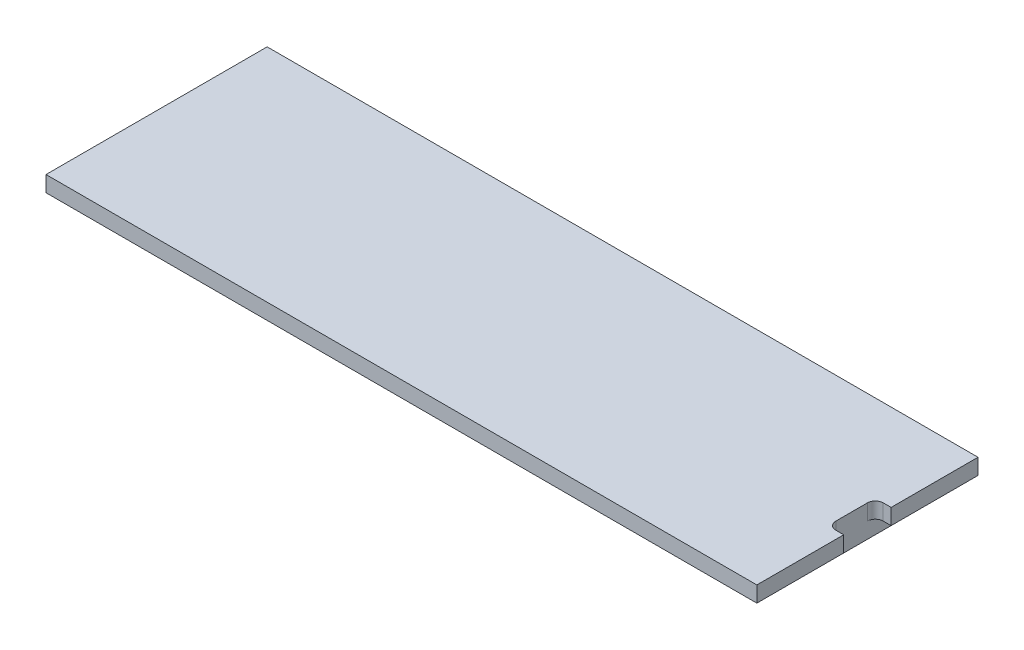
SolidWorks part; units mm, degrees
ref_plane "Front Plane" through (0, 0, 0) normal (0, 0, 1) x (1, 0, 0)
ref_plane "Top Plane" through (0, 0, 0) normal (0, 1, 0) x (1, 0, 0)
ref_plane "Right Plane" through (0, 0, 0) normal (1, 0, 0) x (0, 0, -1)
sketch "Sketch1" plane through (0, 0, 0) normal (0, 1, 0) x (1, 0, 0)
  line L1 (-20.5, -6) -> (20.5, -6)
  line L2 (-21.5, -5) -> (-21.5, 5)
  line L3 (-20.5, 6) -> (20.5, 6)
  line L4 (21.5, -5) -> (21.5, 5)
  line L5 (-21.5, -6) -> (21.5, 6) construction
  line L6 (-21.5, 6) -> (21.5, -6) construction
  arc A0 (21.5, 5) -> (20.5, 6) centre (20.5, 5) ccw
  arc A1 (21.5, -5) -> (20.5, -6) centre (20.5, -5) cw
  arc A2 (-21.5, -5) -> (-20.5, -6) centre (-20.5, -5) ccw
  arc A3 (-21.5, 5) -> (-20.5, 6) centre (-20.5, 5) cw
  point P0 (0, 0)
  dimension "D3" = 1
  dimension "D1" = 43
  dimension "D2" = 12
extrude "Boss-Extrude1" add sketch "Sketch1" along normal blind 1
sketch "Sketch2" plane through (0, 1, 0) normal (0, 1, 0) x (1, 0, 0)
  line L1 (-22.5, -7) -> (22.5, -7)
  line L2 (-22.5, -7) -> (-22.5, 7)
  line L3 (-22.5, 7) -> (22.5, 7)
  line L4 (22.5, -7) -> (22.5, 7)
  line L5 (-22.5, -7) -> (22.5, 7) construction
  line L6 (-22.5, 7) -> (22.5, -7) construction
  point P0 (0, 0)
  dimension "D1" = 45
  dimension "D2" = 14
extrude "Boss-Extrude2" add sketch "Sketch2" along normal blind 1
sketch "Sketch3" plane through (0, 2, 0) normal (0, 1, 0) x (1, 0, 0)
  line L0 (22.5, -7) -> (22.5, 7) construction
  line L2 (21.5, -1.5) -> (21.5, 1.5)
  line L5 (21.5, 1.5) -> (22.5, 1.5)
  line L6 (21.5, -1.5) -> (22.5, -1.5)
  line L7 (22.5, -1.5) -> (22.5, 1.5)
  dimension "D1" = 3
  dimension "D2" = 1
extrude "Cut-Extrude1" cut sketch "Sketch3" against normal blind 1
fillet "Fillet1" radius 0.5 2 edges at (21.5, 1.5, -1.5) (21.5, 1.5, 1.5)
